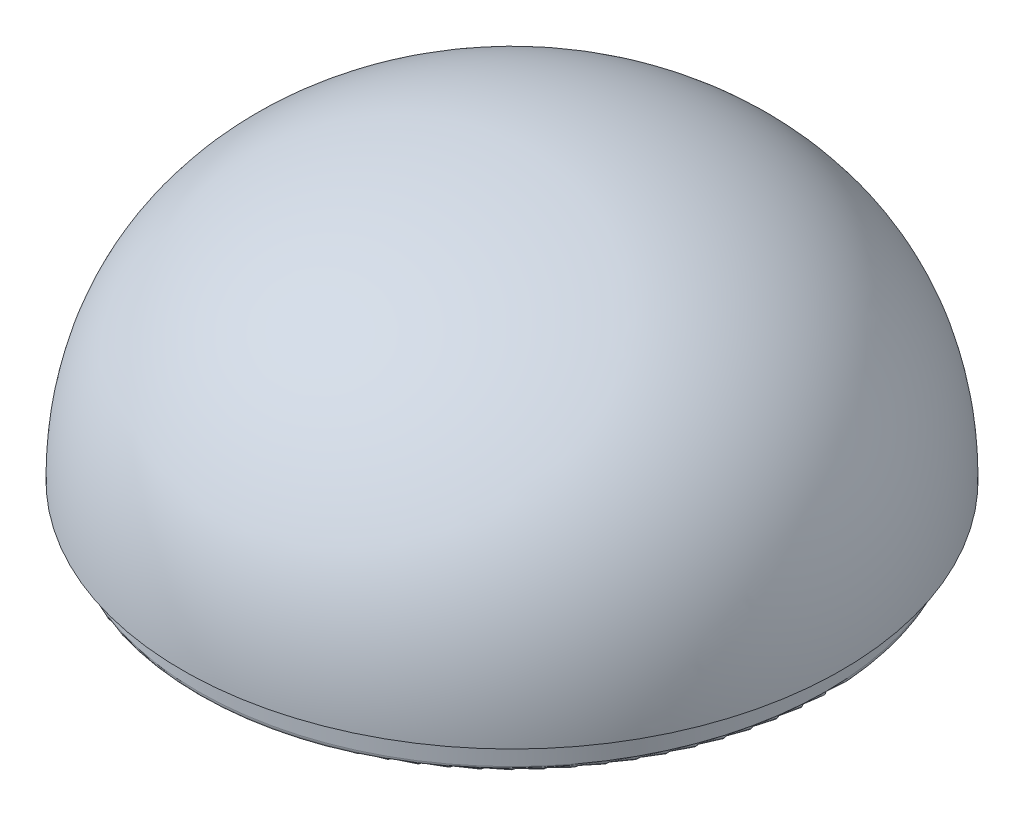
SolidWorks part; units mm, degrees
ref_plane "Front Plane" through (0, 0, 0) normal (0, 0, 1) x (1, 0, 0)
ref_plane "Top Plane" through (0, 0, 0) normal (0, 1, 0) x (1, 0, 0)
ref_plane "Right Plane" through (0, 0, 0) normal (1, 0, 0) x (0, 0, -1)
sketch "Sketch2" plane through (0, 0, 0) normal (0, 0, 1) x (1, 0, 0)
  line L0 (0, 0) -> (0, 54.9189) construction
  line L1 (0, 0) -> (-27.3191, 0) construction
  line L2 (-27.3191, 0) -> (-49.0776, 0) construction
  line L3 (-29.7, 0) -> (-28.7, 0)
  line L4 (-29.7, 0) -> (-29.7, 3)
  line L6 (-28.7, 0) -> (-28.7, 3)
  line L7 (-29.7, 3) -> (-31.2, 3)
  line L8 (-31.2, 18.1453) -> (-31.2, -12.1453) construction
  line L9 (11.8361, 30) -> (-11.8361, 30) construction
  line L10 (-29.7, 4) -> (-30.184, 4)
  line L11 (-29.7, 4) -> (-28.7, 3)
  line L12 (0, 30) -> (0, 29)
  spline S0 degree 3 poles (-31.2, 3) (-31.2, 21.9316) (-14.7951, 30) (0, 30) knots 0 0 0 0 1 1 1 1
  spline S1 degree 1 poles (-30.184, 4) (0, 29) knots 0 0 1 1 construction
  spline S2 degree 3 poles (-30.184, 4) (-30.1666, 4.5407) (-30.1015, 5.6348) (-29.8599, 7.7051) (-29.355, 10.1525) (-28.451, 12.8483) (-26.8803, 16.141) (-24.2888, 19.7079) (-20.3467, 23.1587) (-15.7485, 25.8053) (-10.6895, 27.6667) (-5.3534, 28.7629) (-1.7878, 29) (0, 29) knots 0.018367 0.018367 0.018367 0.018367 0.049043 0.079719 0.141071 0.202423 0.263775 0.386479 0.509183 0.631888 0.754592 0.877296 1 1 1 1
  dimension "D1" = 3
  dimension "D2" = 1
  dimension "D3" = 29.7
  dimension "D4" = 30
  dimension "D6" = 1.5
  dimension "D5" = 1
revolve "Revolve1" add sketch "Sketch2" angle 360 about L0
fillet "Fillet1" radius 0.5 1 edges at (0, 0, -29.7)
